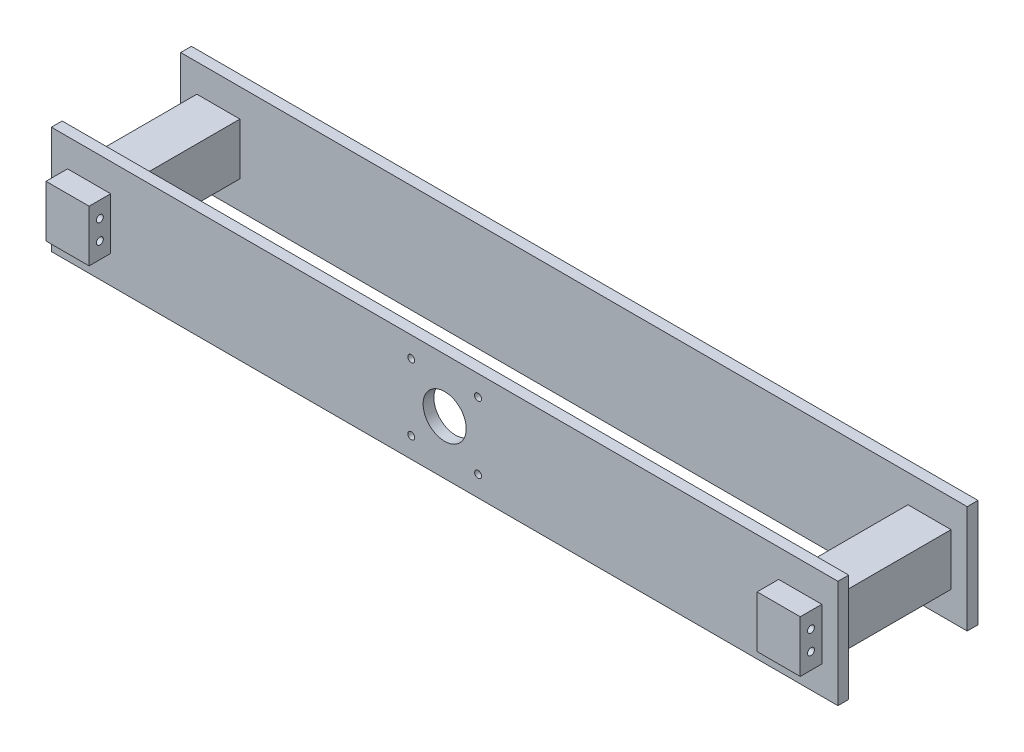
SolidWorks part; units mm, degrees
ref_plane "前视基准面" through (0, 0, 0) normal (0, 0, 1) x (1, 0, 0)
ref_plane "上视基准面" through (0, 0, 0) normal (0, 1, 0) x (1, 0, 0)
ref_plane "右视基准面" through (0, 0, 0) normal (1, 0, 0) x (0, 0, -1)
other "Configuration Table"
sketch "草图1" plane through (0, 0, 0) normal (0, 0, 1) x (1, 0, 0)
  line L0 (0, 0) -> (201.2489, 0) construction
  line L1 (0, 0) -> (0, 177.5446) construction
  line L3 (-182.5, -25) -> (182.5, -25)
  line L4 (-182.5, -25) -> (-182.5, 25)
  line L5 (-182.5, 25) -> (182.5, 25)
  line L6 (182.5, -25) -> (182.5, 25)
  line L7 (-182.5, -25) -> (182.5, 25) construction
  line L8 (-182.5, 25) -> (182.5, -25) construction
  point P1 (0, 0)
  dimension "D1" = 365
  dimension "D2" = 50
extrude "凸台-拉伸1" add sketch "草图1" along normal mid plane 5
sketch "草图2" plane through (0, 0, 2.5) normal (0, 0, 1) x (1, 0, 0)
  line L0 (0, 0) -> (218.2182, 0) construction
  line L1 (0, 0) -> (0, 119.1306) construction
  line L2 (175, -12) -> (155, -12)
  line L3 (-175, -12) -> (-155, -12)
  line L4 (-175, -12) -> (-175, 12)
  line L5 (-175, 12) -> (-155, 12)
  line L6 (-155, -12) -> (-155, 12)
  line L7 (-175, -12) -> (-155, 12) construction
  line L8 (-175, 12) -> (-155, -12) construction
  line L9 (155, -12) -> (155, 12)
  line L10 (175, -12) -> (175, 12)
  line L11 (175, 12) -> (155, 12)
  point P1 (-165, 0)
  dimension "D1" = 24
  dimension "D2" = 350
  dimension "D3" = 20
extrude "凸台-拉伸2" add sketch "草图2" along normal blind 70
pattern_linear "阵列(线性)1" count 2 spacing 60 along (0, 0, 1) of "凸台-拉伸1"
sketch "草图4" plane through (-175, 0, 0) normal (-1, 0, 0) x (0, 0, 1)
  line L0 (0, 0) -> (73.7995, 0) construction
  line L1 (62.5, 25) -> (62.5, -25) construction
  circle A0 centre (67.5, 4.5) radius 1.6
  dimension "D1" = 3.2
  dimension "D2" = 5
  dimension "D3" = 4.5
extrude "切除-拉伸1" cut sketch "草图4" against normal through all contours A0
sketch "草图5" plane through (0, 0, 62.5) normal (0, 0, 1) x (1, 0, 0)
  line L0 (0, 0) -> (187.3411, 0) construction
  line L1 (0, 0) -> (0, 108.1289) construction
  circle A0 centre (-15.5, 15.5) radius 1.6
  circle A1 centre (15.5, 15.5) radius 1.6
  circle A2 centre (15.5, -15.5) radius 1.6
  circle A3 centre (-15.5, -15.5) radius 1.6
  circle A4 centre (0, 0) radius 10
  point P15 (0, 0)
  dimension "D1" = 3.2
  dimension "D5" = 20
  dimension "D2" = 15.5
  dimension "D3" = 15.5
  dimension "D4" = 4
extrude "切除-拉伸2" cut sketch "草图5" against normal up to next
mirror "镜向1" about plane through (0, 0, 0) normal (0, 1, 0) of "切除-拉伸1"
